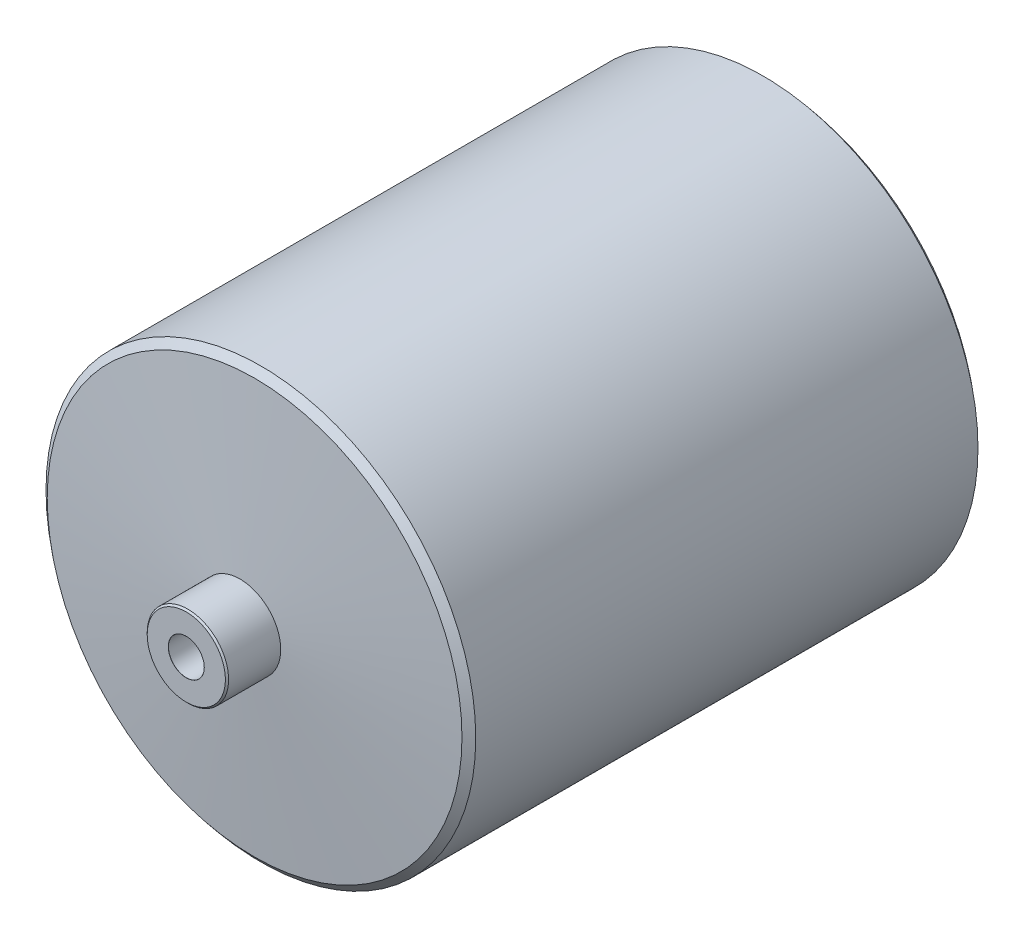
SolidWorks part; units mm, degrees
ref_plane "Front Plane" through (0, 0, 0) normal (0, 0, 1) x (1, 0, 0)
ref_plane "Top Plane" through (0, 0, 0) normal (0, 1, 0) x (1, 0, 0)
ref_plane "Right Plane" through (0, 0, 0) normal (1, 0, 0) x (0, 0, -1)
sketch "Sketch1" plane through (0, 0, 0) normal (1, 0, 0) x (0, 0, -1)
  line L0 (-100, 0) -> (100, 0)
  line L1 (77.0975, 65.9675) -> (-77.0975, 65.9675)
  line L2 (-77.0975, 65.9675) -> (-79.0234, 63.6673)
  line L3 (-79.0234, 63.6673) -> (-79.0234, 19.212) construction
  line L4 (-79.0234, 63.6673) -> (-83.5, 12.5)
  line L5 (-83.5, 12.5) -> (-100, 12.5)
  line L6 (-100, 12.5) -> (-100, 0)
  line L7 (0, 0) -> (0, 30.671) construction
  line L8 (79.0234, 63.6673) -> (79.0234, 19.212) construction
  line L9 (100, 12.5) -> (100, 0)
  line L10 (83.5, 12.5) -> (100, 12.5)
  line L11 (79.0234, 63.6673) -> (83.5, 12.5)
  line L12 (77.0975, 65.9675) -> (79.0234, 63.6673)
  point P4 (0, 0)
  point P20 (0, 65.9675)
  dimension "D1" = 12.5
  dimension "D2" = 100
  dimension "D3" = 3
  dimension "D4" = 16.5
  dimension "D5" = 85
revolve "Revolve1" add sketch "Sketch1" angle 360 about L0
sketch "Sketch5" plane through (0, 0, 100) normal (0, 0, 1) x (1, 0, 0)
  point P0 (0, 0)
sketch "Sketch6" plane through (0, 0, -100) normal (0, 0, -1) x (-1, 0, 0)
  point P0 (0, 0)
hole_wizard "M10 Clearance Hole2" positions "3DSketch5" profile "Sketch8" hole size "M10" standard "ANSI Metric"
sketch3d "3DSketch5"
  point P0 (0, 0, -100)
  point P3 (0, 0, 100)
sketch "Sketch8" plane through (0, 0, -100) normal (1, 0, 0) x (0, 1, 0)
  line L0 (0, 0) -> (0, 59)
  line L1 (0, 59) -> (5.5, 55.6953)
  line L2 (5.5, 55.6953) -> (5.5, 0.025)
  line L3 (5.5, 0.025) -> (5.525, 0)
  line L5 (5.525, 0) -> (0, 0)
  line L6 (-5.5, 0.025) -> (-5.525, 0) construction
  line L10 (0, 59) -> (-5.5, 55.6953) construction
  line L11 (0, -6.35) -> (0, 107.95) construction
  dimension "Hole Dia." = 11
  dimension "Hole Depth" = 59
  dimension "Near C'Sink Dia." = 11.05
  dimension "Near C'Sink Angle" = 90
  dimension "Drill Angle" = 118
chamfer "Chamfer1" distance 0.5 angle 45 2 edges at (12.5, 0, -100) (12.5, 0, 100)
